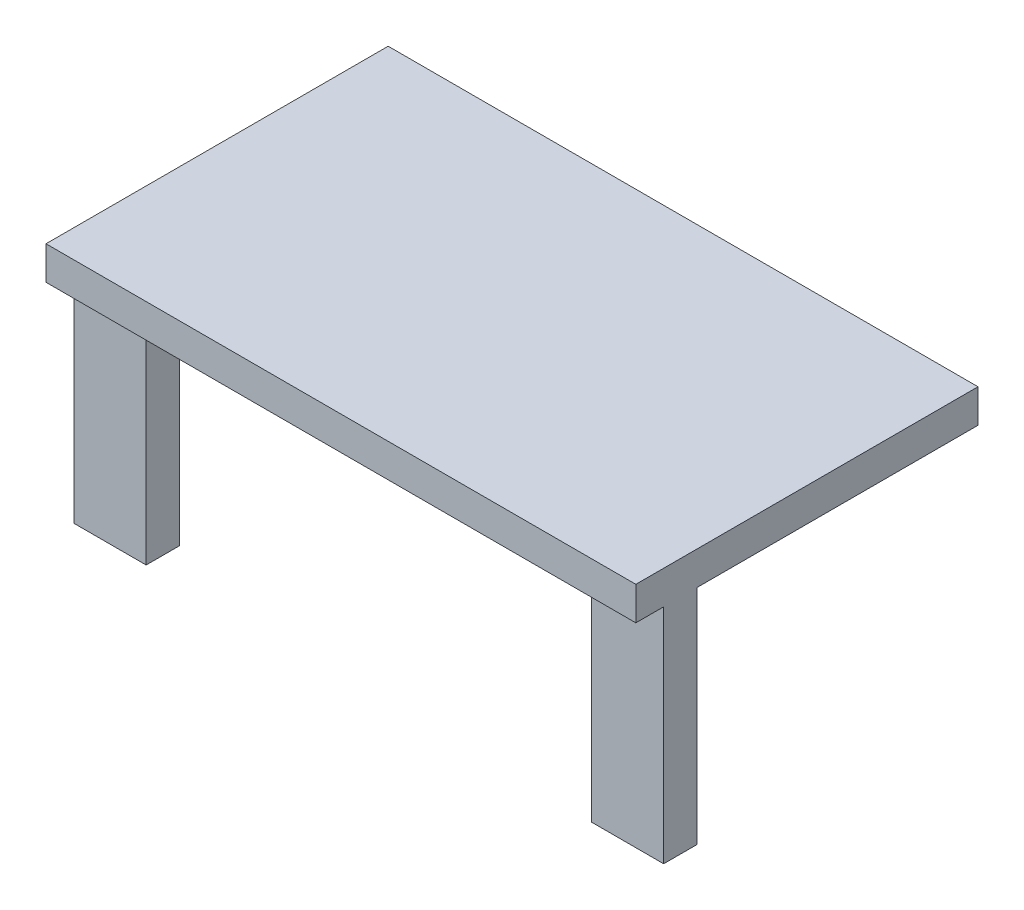
SolidWorks part; units mm, degrees
ref_plane "Front Plane" through (0, 0, 0) normal (0, 0, 1) x (1, 0, 0)
ref_plane "Top Plane" through (0, 0, 0) normal (0, 1, 0) x (1, 0, 0)
ref_plane "Right Plane" through (0, 0, 0) normal (1, 0, 0) x (0, 0, -1)
sketch "Sketch1" plane through (0, 0, 0) normal (0, 1, 0) x (1, 0, 0)
  line L1 (-2.3819, -6.7453) -> (50.6181, -6.7453)
  line L2 (-2.3819, -6.7453) -> (-2.3819, -37.4909)
  line L3 (-2.3819, -37.4909) -> (50.6181, -37.4909)
  line L4 (50.6181, -6.7453) -> (50.6181, -37.4909)
  dimension "D1" = 30.7456
  dimension "D2" = 53
extrude "Boss-Extrude1" add sketch "Sketch1" along normal blind 3
sketch "Sketch2" plane through (0, 0, 0) normal (0, -1, 0) x (1, 0, 0)
  line L0 (50.6181, 37.4909) -> (50.6181, 6.7453) construction
  line L1 (50.6181, 34.9909) -> (44.1181, 34.9909)
  line L2 (50.6181, 34.9909) -> (50.6181, 31.9909)
  line L3 (50.6181, 31.9909) -> (44.1181, 31.9909)
  line L4 (44.1181, 34.9909) -> (44.1181, 31.9909)
  line L5 (48.8065, 34.9909) -> (50.6181, 34.9909) construction
  line L6 (44.1181, 23.4909) -> (44.1181, 52.9909) construction
  line L7 (-2.3819, 6.7453) -> (-2.3819, 37.4909) construction
  line L8 (4.1181, 34.9909) -> (-2.3819, 34.9909)
  line L9 (4.1181, 34.9909) -> (4.1181, 31.9909)
  line L10 (4.1181, 31.9909) -> (-2.3819, 31.9909)
  line L11 (-2.3819, 34.9909) -> (-2.3819, 31.9909)
  dimension "D1" = 3
  dimension "D2" = 3
extrude "Boss-Extrude2" add sketch "Sketch2" along normal blind 20
